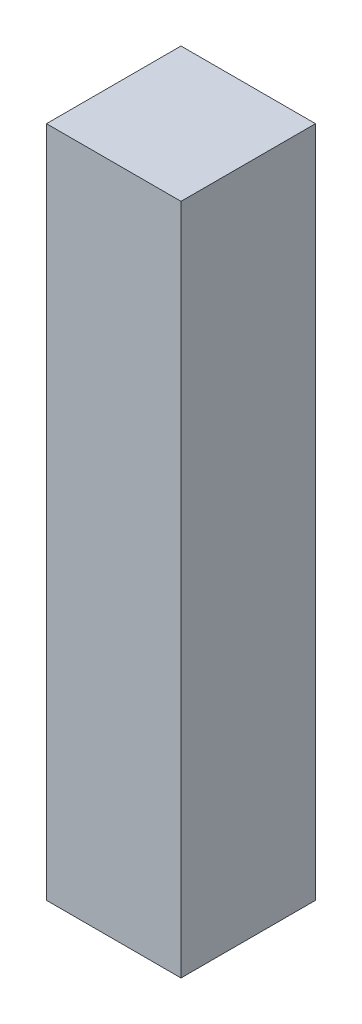
SolidWorks part; units mm, degrees
ref_plane "Front Plane" through (0, 0, 0) normal (0, 0, 1) x (1, 0, 0)
ref_plane "Top Plane" through (0, 0, 0) normal (0, 1, 0) x (1, 0, 0)
ref_plane "Right Plane" through (0, 0, 0) normal (1, 0, 0) x (0, 0, -1)
sketch "Sketch1" plane through (0, 0, 0) normal (0, 1, 0) x (1, 0, 0)
  line L1 (-20, 20) -> (20, 20)
  line L2 (-20, 20) -> (-20, -20)
  line L3 (-20, -20) -> (20, -20)
  line L4 (20, 20) -> (20, -20)
  line L5 (-20, 20) -> (20, -20) construction
  line L6 (-20, -20) -> (20, 20) construction
  point P0 (0, 0)
  dimension "D1" = 40
  dimension "D2" = 40
extrude "Boss-Extrude1" add sketch "Sketch1" along normal blind 200
equation "\"height\"= 200"
equation "\"depth\"= 600"
equation "\"width\"= 600"
equation "\"section width\"= 40"
equation "\"D1@Sketch1\"=\"section width\""
equation "\"D2@Sketch1\"=\"section width\""
equation "\"D1@Boss-Extrude1\"=\"height\""
